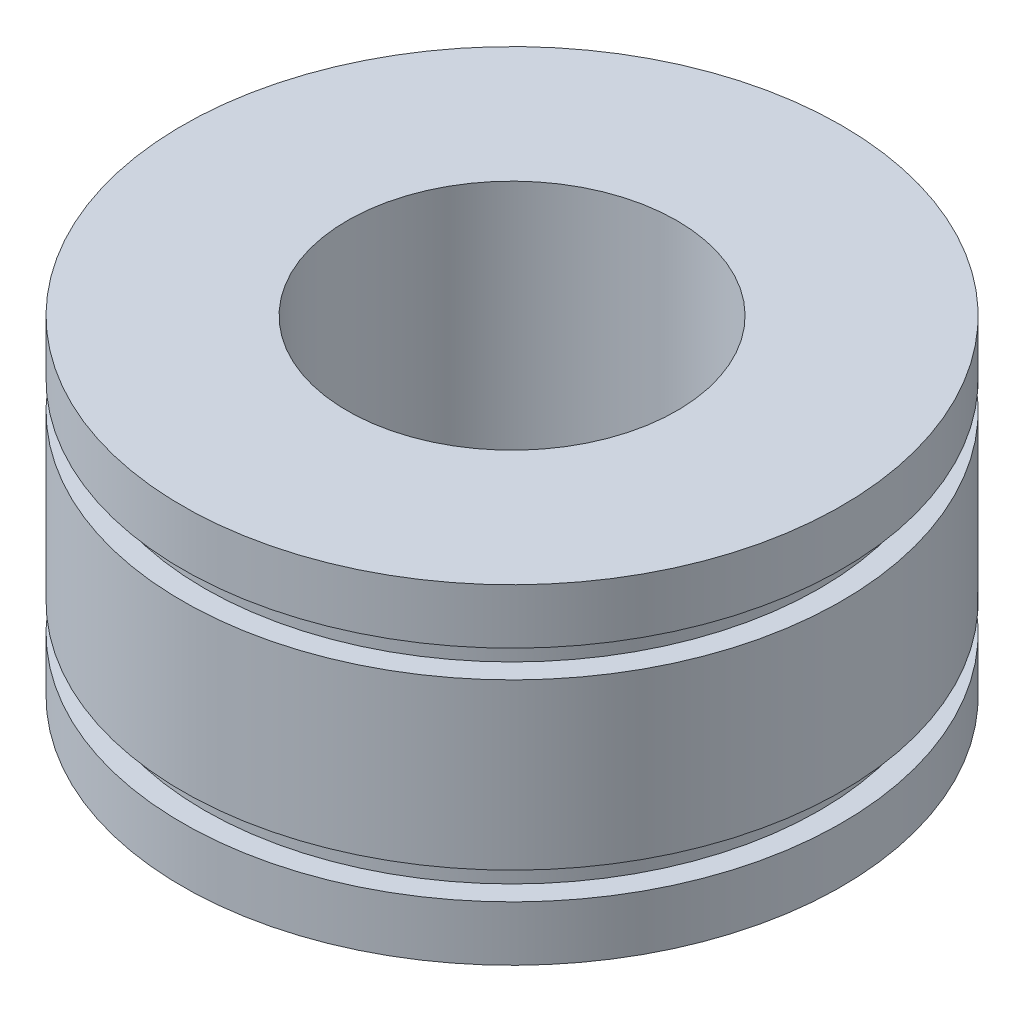
SolidWorks part; units mm, degrees
ref_plane "前视基准面" through (0, 0, 0) normal (0, 0, 1) x (1, 0, 0)
ref_plane "上视基准面" through (0, 0, 0) normal (0, 1, 0) x (1, 0, 0)
ref_plane "右视基准面" through (0, 0, 0) normal (1, 0, 0) x (0, 0, -1)
sketch "草图1" plane through (0, 0, 0) normal (0, 0, 1) x (1, 0, 0)
  line L0 (0, 0) -> (0, 3)
  line L1 (0, 3) -> (3, 3)
  line L2 (3, 3) -> (3, 2.5)
  line L3 (3, 2.5) -> (2.8, 2.5)
  line L4 (2.8, 2.5) -> (2.8, 2.25)
  line L5 (2.8, 2.25) -> (3, 2.25)
  line L6 (3, 2.25) -> (3, 0.75)
  line L7 (3, 0.75) -> (2.8, 0.75)
  line L8 (2.8, 0.75) -> (2.8, 0.5)
  line L9 (2.8, 0.5) -> (3, 0.5)
  line L10 (3, 0.5) -> (3, 0)
  line L11 (3, 0) -> (0, 0)
  line L12 (0, 1.5) -> (3, 1.5) construction
  line L14 (0, 3) -> (1.5, 3)
  line L15 (0, 3) -> (0, 0)
  line L16 (0, 0) -> (1.5, 0)
  line L17 (1.5, 3) -> (1.5, 0)
  dimension "D1" = 3
  dimension "D2" = 3
  dimension "D3" = 0.2
  dimension "D4" = 2
  dimension "D5" = 1.5
  dimension "D6" = 1.5
revolve "旋转1" add sketch "草图1" angle 360 about L0
